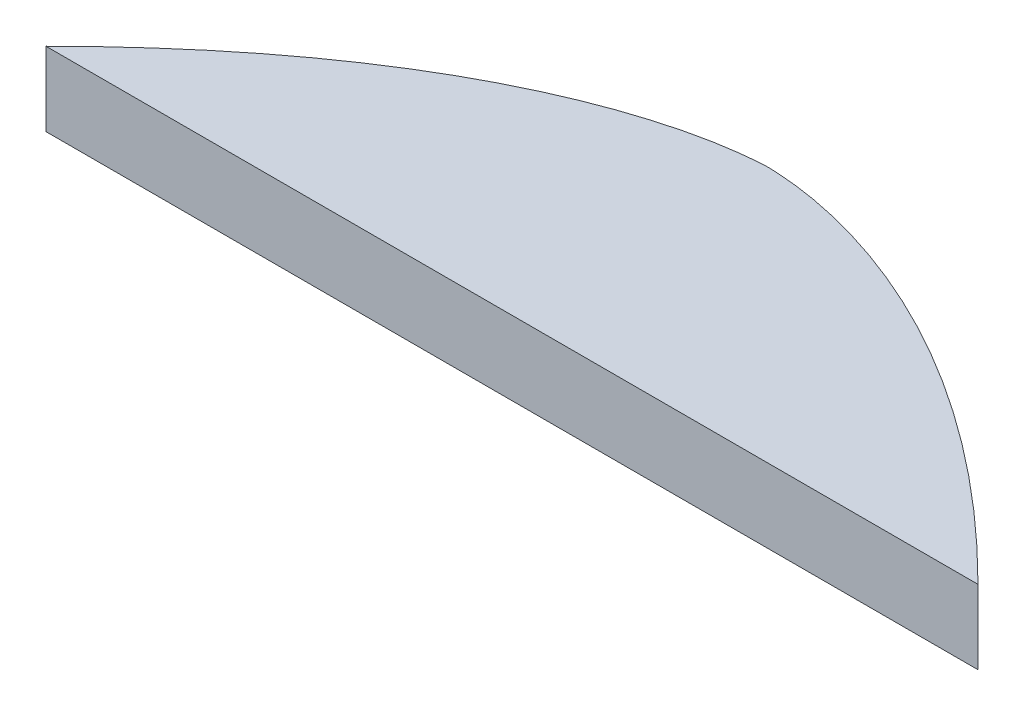
SolidWorks part; units mm, degrees
ref_plane "Front Plane" through (0, 0, 0) normal (0, 0, 1) x (1, 0, 0)
ref_plane "Top Plane" through (0, 0, 0) normal (0, 1, 0) x (1, 0, 0)
ref_plane "Right Plane" through (0, 0, 0) normal (1, 0, 0) x (0, 0, -1)
sketch "Sketch1" plane through (0, 0, 0) normal (0, 1, 0) x (1, 0, 0)
  line L0 (0, 0) -> (40, 0)
  line L1 (0, 0) -> (-40, 0)
  line L2 (0, 0) -> (0, 22) construction
  line L3 (158.006, -118.006) -> (-80.006, 120.006) construction
  line L4 (195.4238, 235.4238) -> (-266.3903, -226.3903) construction
  line L5 (75.6719, 22) -> (-75.6719, 22) construction
  spline S0 degree 3 poles (-40, 0) (-18.7868, 21.2132) (0.9663, 21.9831) (-0.9168, 22.027) (18.7868, 21.2132) (40, 0) knots 0 0 0 0 0.255671 0.308531 0.528598 0.528598 0.528598 0.528598
  dimension "D4" = 45
  dimension "D5" = 100
  dimension "D6" = 45
  dimension "D7" = 100
  dimension "D8" = 90
  dimension "D9" = 5
  dimension "D1" = 40
  dimension "D3" = 22
extrude "Boss-Extrude1" add sketch "Sketch1" along normal blind 6.35
